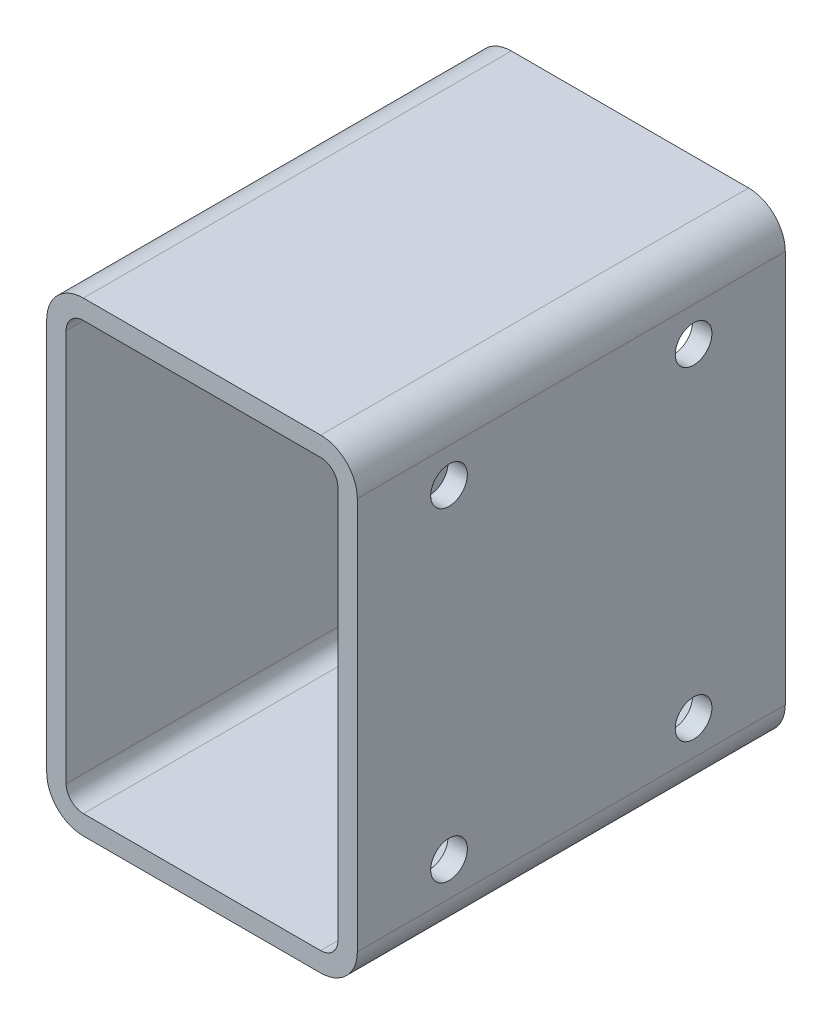
SolidWorks part; units mm, degrees
material "Plain Carbon Steel"
ref_plane "Front Plane" through (0, 0, 0) normal (0, 0, 1) x (1, 0, 0)
ref_plane "Top Plane" through (0, 0, 0) normal (0, 1, 0) x (1, 0, 0)
ref_plane "Right Plane" through (0, 0, 0) normal (1, 0, 0) x (0, 0, -1)
sketch "Sketch1" plane through (0, 0, 0) normal (0, 0, 1) x (1, 0, 0)
  line L0 (19.4, 34.925) -> (-19.4, 34.925)
  line L1 (19.4, -38.1) -> (-19.4, -38.1)
  line L2 (25.4, -32.1) -> (25.4, 32.1)
  line L3 (19.4, 38.1) -> (-19.4, 38.1)
  line L4 (-25.4, -32.1) -> (-25.4, 32.1)
  line L5 (25.4, -38.1) -> (-25.4, 38.1) construction
  line L6 (25.4, 38.1) -> (-25.4, -38.1) construction
  line L7 (-22.225, -32.1) -> (-22.225, 32.1)
  line L8 (19.4, -34.925) -> (-19.4, -34.925)
  line L9 (22.225, -32.1) -> (22.225, 32.1)
  arc A0 (-19.4, -38.1) -> (-25.4, -32.1) centre (-19.4, -32.1) cw
  arc A1 (19.4, -38.1) -> (25.4, -32.1) centre (19.4, -32.1) ccw
  arc A2 (25.4, 32.1) -> (19.4, 38.1) centre (19.4, 32.1) ccw
  arc A3 (-19.4, 38.1) -> (-25.4, 32.1) centre (-19.4, 32.1) ccw
  arc A4 (-19.4, 34.925) -> (-22.225, 32.1) centre (-19.4, 32.1) ccw
  arc A5 (-19.4, -34.925) -> (-22.225, -32.1) centre (-19.4, -32.1) cw
  arc A6 (19.4, -34.925) -> (22.225, -32.1) centre (19.4, -32.1) ccw
  arc A7 (22.225, 32.1) -> (19.4, 34.925) centre (19.4, 32.1) ccw
  point P0 (0, 0)
  dimension "D1" = 6
  dimension "D3" = 76.2
  dimension "D4" = 50.8
  dimension "D2" = 3.175
extrude "Boss-Extrude1" add sketch "Sketch1" along normal mid plane 70
sketch "Sketch2" plane through (25.4, 0, 0) normal (1, 0, 0) x (0, 0, -1)
  line L1 (20, -26.5) -> (-20, -26.5) construction
  line L2 (20, -26.5) -> (20, 26.5) construction
  line L3 (20, 26.5) -> (-20, 26.5) construction
  line L4 (-20, -26.5) -> (-20, 26.5) construction
  line L5 (20, -26.5) -> (-20, 26.5) construction
  line L6 (20, 26.5) -> (-20, -26.5) construction
  circle A0 centre (-20, 26.5) radius 3
  circle A1 centre (20, 26.5) radius 3
  circle A2 centre (20, -26.5) radius 3
  circle A3 centre (-20, -26.5) radius 3
  point P0 (0, 0)
  dimension "D3" = 6
  dimension "D1" = 40
  dimension "D2" = 53
extrude "Cut-Extrude1" cut sketch "Sketch2" against normal blind 10
equation "\"M5_tap\"=4.2mm\t\t\t\t\t\t\t' Below you can do mesurements as follows: cm, mm, ft, in, m, "
equation "\"M5_clearence\"=5.5mm"
equation "\"M6_tap\"=5mm"
equation "\"M6_clearence\"=6.6mm"
equation "\"work_area_width\"=1100mm"
equation "\"work_area_depth\"=900mm"
equation "\"D3@Sketch1\"=\"steel_rollers_width\""
equation "\"D4@Sketch1\"=\"steel_rollers_height\""
equation "\"D1@Sketch1\"=\"steel_rollers_radius\""
equation "\"D2@Sketch1\"=\"steel_rollers_wall_thickness\""
equation "\"D1@Boss-Extrude1\"=\"work_area_depth\" + 200"
equation "\"steel_base_width\"=3in\t"
equation "\"steel_base_height\"=2in"
equation "\"steel_base_wall_thickness\"=0.125in"
equation "\"steel_base_radius\"=6mm"
equation "\"steel_sides_width\"=3in\t\t\t\t\t'this tube is rotated so flip width/height"
equation "\"steel_sides_height\"=2in\t\t\t\t'this tube is rotated so flip width/height"
equation "\"steel_sides_wall_thickness\"=0.125in"
equation "\"steel_sides_radius\"=6mm"
equation "\"steel_gantry_width\"=4in\t\t\t\t'this tube is rotated so flip width/height"
equation "\"steel_gantry_height\"=3in\t\t\t\t'this tube is rotated so flip width/height"
equation "\"steel_gantry_wall_thickness\"=0.125in"
equation "\"steel_gantry_radius\"=6mm"
equation "\"steel_rollers_width\"=3in"
equation "\"steel_rollers_height\"=2in\t\t\t\t'keep as low as possible as this increases how big plastic parts are"
equation "\"steel_rollers_wall_thickness\"=0.125in"
equation "\"steel_rollers_radius\"=6mm"
equation "\"steel_zbox_width\"=4in\t\t\t\t\t'if the gantry height (rotated) is too thick, a wider zbox is necessary"
equation "\"steel_zbox_height\"=2in\t\t\t\t\t'hole patteren changes as the zbox and gantry height (rotated) changes."
equation "\"steel_zbox_wall_thickness\"=0.125in"
equation "\"steel_zbox_radius\"=6mm"
